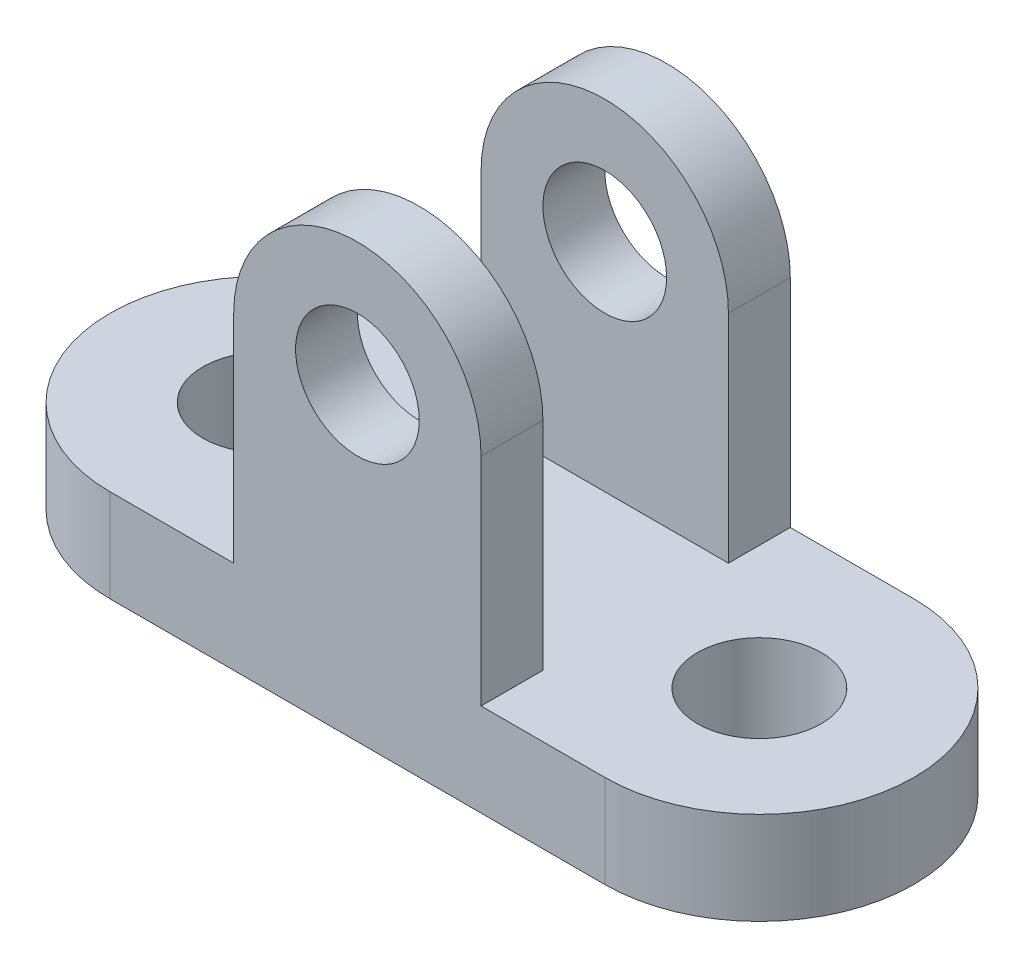
SolidWorks part; units mm, degrees
ref_plane "Front Plane" through (0, 0, 0) normal (0, 0, 1) x (1, 0, 0)
ref_plane "Top Plane" through (0, 0, 0) normal (0, 1, 0) x (1, 0, 0)
ref_plane "Right Plane" through (0, 0, 0) normal (1, 0, 0) x (0, 0, -1)
sketch "Sketch2" plane through (0, 0, 0) normal (0, 1, 0) x (1, 0, 0)
  line L0 (-40, 0) -> (40, 0) construction
  line L1 (-40, 25) -> (40, 25)
  line L2 (-40, -25) -> (40, -25)
  arc A0 (-40, 25) -> (-40, -25) centre (-40, 0) ccw
  arc A1 (40, -25) -> (40, 25) centre (40, 0) ccw
  circle A2 centre (-40, 0) radius 10
  circle A3 centre (40, 0) radius 10
  point P2 (0, 0)
  dimension "D1" = 20
  dimension "D2" = 25
  dimension "D3" = 80
extrude "Boss-Extrude1" add sketch "Sketch2" along normal blind 15
sketch "Sketch3" plane through (0, 0, 0) normal (0, 0, 1) x (1, 0, 0)
  line L0 (-20, 15) -> (-20, 50)
  line L1 (-40, 15) -> (40, 15) construction
  line L2 (20, 50) -> (20, 15)
  line L3 (-20, 15) -> (20, 15)
  arc A0 (-20, 50) -> (20, 50) centre (0, 50) cw
  circle A1 centre (0, 50) radius 10
  point P8 (0, 70)
  dimension "D2" = 20
  dimension "D3" = 20
  dimension "D1" = 35
extrude "Boss-Extrude2" add sketch "Sketch3" along normal blind 10 from offset 15
mirror "Mirror1" about plane through (0, 0, 0) normal (0, 0, 1) of "Boss-Extrude2"
